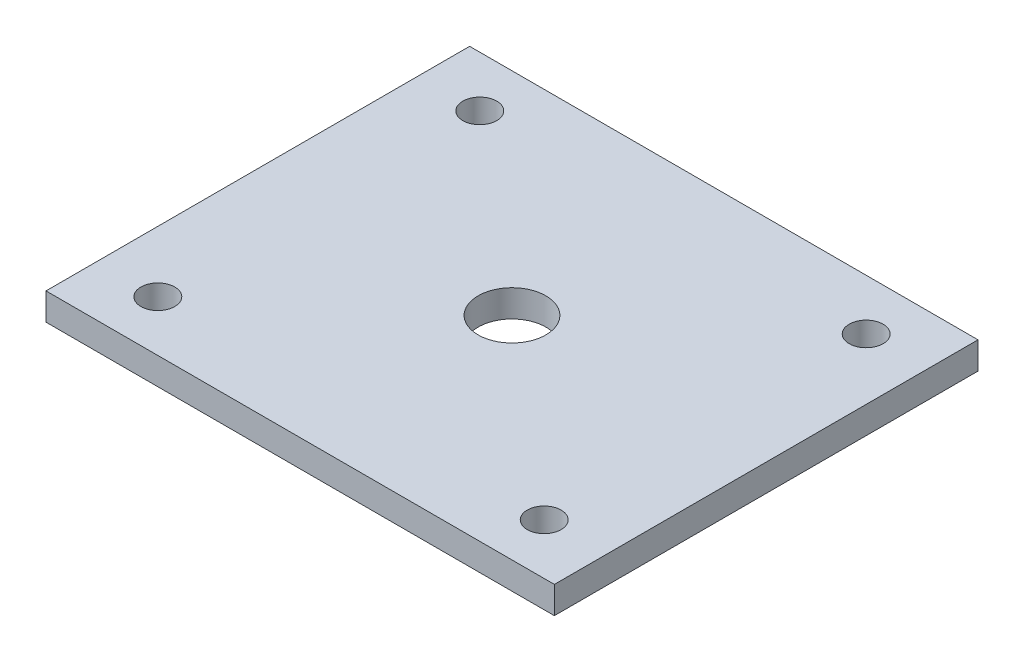
SolidWorks part; units mm, degrees
ref_plane "Front Plane" through (0, 0, 0) normal (0, 0, 1) x (1, 0, 0)
ref_plane "Top Plane" through (0, 0, 0) normal (0, 1, 0) x (1, 0, 0)
ref_plane "Right Plane" through (0, 0, 0) normal (1, 0, 0) x (0, 0, -1)
sketch "Sketch2" plane through (0, 0, 0) normal (0, 1, 0) x (1, 0, 0)
  line L0 (-15, 0) -> (15, 0) construction
  line L1 (-15, 12.5) -> (15, 12.5)
  line L2 (-15, 12.5) -> (-15, -12.5)
  line L3 (-15, -12.5) -> (15, -12.5)
  line L4 (15, 12.5) -> (15, -12.5)
  line L5 (-15, 12.5) -> (15, -12.5) construction
  line L6 (-15, -12.5) -> (15, 12.5) construction
  circle A0 centre (-11.4, 9.5) radius 1
  circle A1 centre (11.4, 9.5) radius 1
  circle A2 centre (11.4, -9.5) radius 1
  circle A3 centre (-11.4, -9.5) radius 1
  circle A4 centre (0, 0) radius 2
  point P0 (0, 0)
  point P13 (0, 0)
  dimension "D3" = 2
  dimension "D5" = 3.6
  dimension "D7" = 4
  dimension "D1" = 30
  dimension "D2" = 25
  dimension "D4" = 3
  dimension "D6" = 2
extrude "Boss-Extrude1" add sketch "Sketch2" along normal blind 1.6 contours L1 L4 L3 L2
